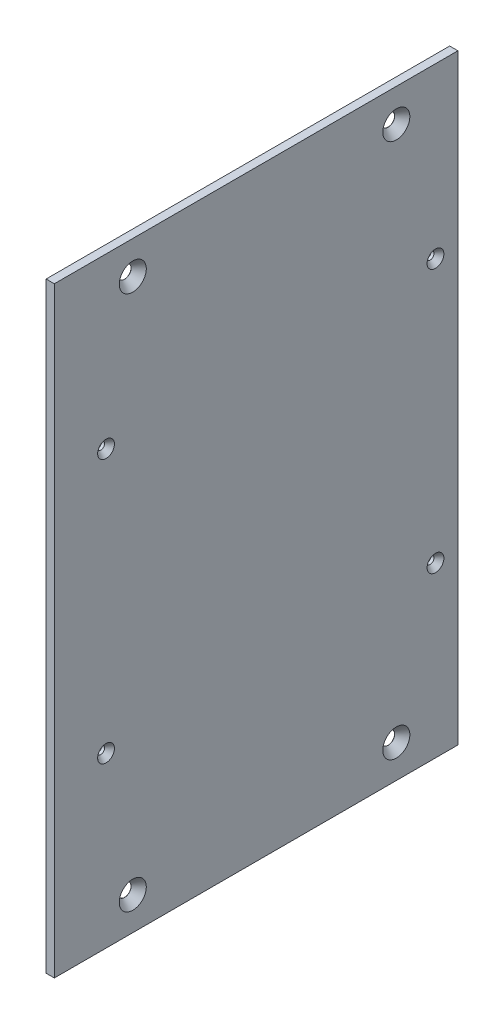
SolidWorks part; units mm, degrees
ref_plane "Front Plane" through (0, 0, 0) normal (0, 0, 1) x (1, 0, 0)
ref_plane "Top Plane" through (0, 0, 0) normal (0, 1, 0) x (1, 0, 0)
ref_plane "Right Plane" through (0, 0, 0) normal (1, 0, 0) x (0, 0, -1)
sketch "Sketch1" plane through (19.05, 0, 0) normal (1, 0, 0) x (0, 1, 0)
  line L0 (24.3095, 180.84) -> (-207.4655, 180.84)
  line L6 (-207.4655, 180.84) -> (-207.4655, 25.265)
  line L7 (-207.4655, 25.265) -> (24.3095, 25.265)
  line L8 (24.3095, 25.265) -> (24.3095, 180.84)
  dimension "D1" = 155.575
extrude "Boss-Extrude1" add sketch "Sketch1" along normal blind 3.175
sketch "Sketch9" plane through (22.225, 0, 12.573) normal (-1, 0, 0) x (0, 0, -1)
  line L1 (-21.3375, 142.378) -> (-21.3375, 40.778) construction
  line L2 (-21.3375, 40.778) -> (-148.3375, 40.778) construction
  line L3 (-148.3375, 40.778) -> (-148.3375, 142.378) construction
  line L4 (-148.3375, 142.378) -> (-21.3375, 142.378) construction
  point P0 (-148.3375, 142.378)
  dimension "D1" = 0
  dimension "D2" = 0
sketch "Sketch3" plane through (19.05, 0, 0) normal (-1, 0, 0) x (0, 1, 0)
  line L0 (11.6095, -150.6006) -> (11.6095, -49.0006) construction
  line L1 (11.6095, -49.0006) -> (-194.7655, -49.0006) construction
  line L2 (-194.7655, -49.0006) -> (-194.7655, -150.6006) construction
  line L3 (-194.7655, -150.6006) -> (11.6095, -150.6006) construction
  point P8 (0, 0)
  point P9 (0, 0)
  point P10 (0, 0)
  point P11 (0, 0)
hole_wizard "#10 Clearance Hole1" positions "Sketch4" profile "Sketch5" hole size "#10" standard "ANSI Inch" end condition through all
sketch "Sketch4" plane through (19.05, 0, 0) normal (-1, 0, 0) x (0, 1, 0)
  point P0 (-194.7655, -150.6006)
  point P3 (-194.7655, -49.0006)
  point P6 (11.6095, -49.0006)
  point P9 (11.6095, -150.6006)
sketch "Sketch5" plane through (19.05, -194.7655, 150.6006) normal (0, 1, 0) x (0, 0, 1)
  line L0 (0, 0) -> (0, 3.175)
  line L1 (0, 3.175) -> (5.207, 3.175)
  line L2 (2.4892, 0.0485) -> (2.4892, 0)
  line L5 (2.4892, 0) -> (0, 0)
  line L7 (5.207, 3.175) -> (2.4892, 0.0485)
  line L8 (-5.207, 3.175) -> (-2.4892, 0.0485) construction
  line L11 (0, -6.35) -> (0, 107.95) construction
  dimension "Thru Hole Dia." = 4.9784
  dimension "Thru Hole Depth" = 3.175
  dimension "Far C'Sink Dia." = 10.414
  dimension "Far C'Sink Angle" = 82
hole_wizard "#4 Clearance Hole1" positions "Sketch10" profile "Sketch11" hole size "#4" standard "ANSI Inch" end condition through all
sketch "Sketch10" plane through (22.225, 0, 0) normal (1, 0, 0) x (0, -1, 0)
  point P0 (40.778, -160.9105)
  point P3 (142.378, -160.9105)
  point P6 (142.378, -33.9105)
  point P9 (40.778, -33.9105)
sketch "Sketch11" plane through (22.225, -40.778, 160.9105) normal (0, 1, 0) x (0, 0, -1)
  line L0 (0, 0) -> (0, 3.175)
  line L1 (0, 3.175) -> (1.4732, 3.175)
  line L2 (1.4732, 3.175) -> (1.4732, 2.0307)
  line L3 (1.4732, 2.0307) -> (3.2385, 0)
  line L5 (3.2385, 0) -> (0, 0)
  line L6 (-1.4732, 2.0307) -> (-3.2385, 0) construction
  line L11 (0, -6.35) -> (0, 107.95) construction
  dimension "Thru Hole Dia." = 2.9464
  dimension "Thru Hole Depth" = 3.175
  dimension "Near C'Sink Dia." = 6.477
  dimension "Near C'Sink Angle" = 82
